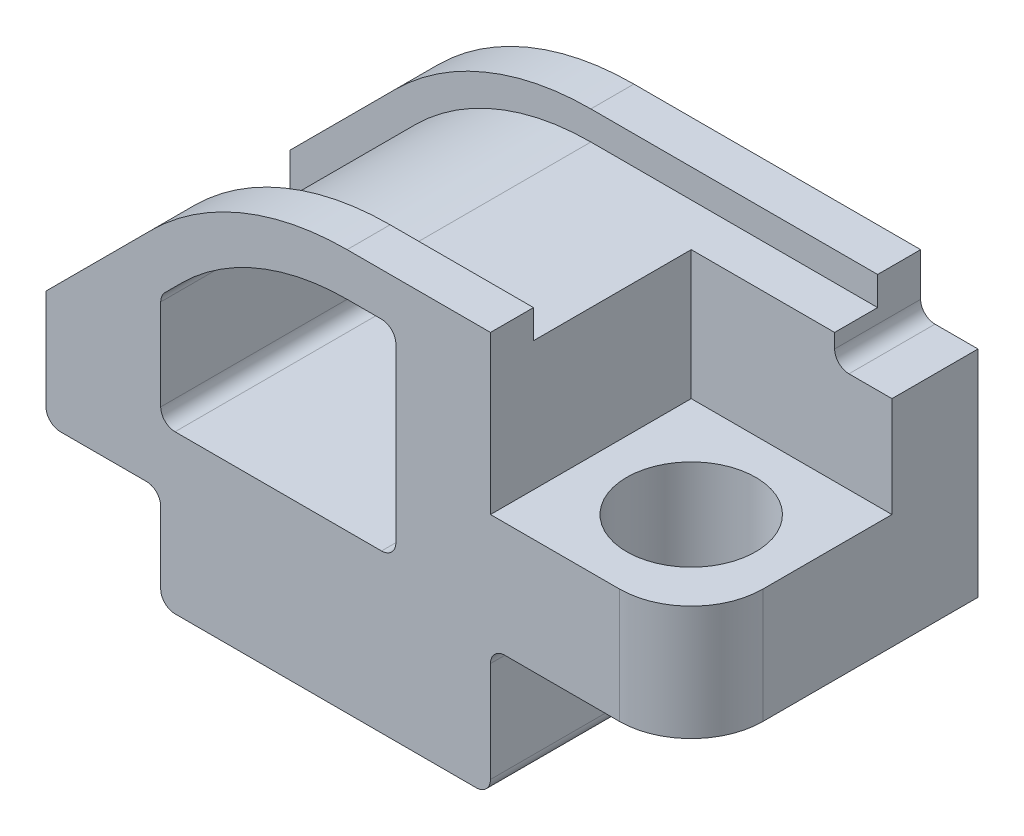
SolidWorks part; units mm, degrees
material "Copper"
ref_plane "Front Plane" through (0, 0, 0) normal (0, 0, 1) x (1, 0, 0)
ref_plane "Top Plane" through (0, 0, 0) normal (0, 1, 0) x (1, 0, 0)
ref_plane "Right Plane" through (0, 0, 0) normal (1, 0, 0) x (0, 0, -1)
sketch "Sketch1" plane through (0, 0, 0) normal (0, 0, 1) x (1, 0, 0)
  line L0 (0, 0) -> (40, 0)
  line L1 (40, 0) -> (40, -35)
  line L2 (40, -35) -> (155, -35)
  line L3 (155, -35) -> (155, 10)
  line L4 (155, 10) -> (225, 10)
  line L5 (225, 10) -> (225, 85)
  line L6 (225, 85) -> (205, 85)
  line L7 (205, 85) -> (205, 105)
  line L8 (205, 105) -> (105, 105)
  line L9 (36.7157, 76.7157) -> (0, 40)
  line L10 (0, 40) -> (0, 0)
  arc A0 (105, 105) -> (36.7157, 76.7157) centre (105, 8.4315) ccw
  point P14 (155, 105)
  point P15 (32.6613, 85)
  dimension "D1" = 35
  dimension "D2" = 115
  dimension "D3" = 45
  dimension "D4" = 70
  dimension "D5" = 75
  dimension "D6" = 140
  dimension "D7" = 20
  dimension "D8" = 100
  dimension "D9" = 225
  dimension "D10" = 40
  dimension "D11" = 45
extrude "Boss-Extrude1" add sketch "Sketch1" along normal mid plane 100
sketch "Sketch2" plane through (0, 0, 50) normal (0, 0, 1) x (1, 0, 0)
  line L15 (40, 58.7868) -> (40, 20)
  line L16 (40, 20) -> (122, 20)
  line L17 (205, 90) -> (105, 90)
  line L18 (47.3223, 66.1091) -> (10.6066, 29.3934)
  line L19 (122, 90) -> (105, 90)
  line L20 (47.3223, 66.1091) -> (40, 58.7868)
  line L21 (122, 20) -> (122, 90)
  line L22 (155, -35) -> (155, 10) construction
  line L23 (40, 0) -> (40, -35) construction
  line L24 (0, 40) -> (0, 0) construction
  arc A4 (105, 90) -> (47.3223, 66.1091) centre (105, 8.4315) ccw
  arc A5 (105, 90) -> (47.3223, 66.1091) centre (105, 8.4315) ccw
  point P10 (0, 20)
  dimension "D2" = 33
  dimension "D1" = 15
extrude "Cut-Extrude1" cut sketch "Sketch2" against normal through all
sketch "Sketch5" plane through (0, 0, 0) normal (0, 0, 1) x (1, 0, 0)
  line L2 (205, 85) -> (205, 105) construction
  line L3 (205, 105) -> (105, 105) construction
  line L4 (205, 95) -> (105, 95)
  line L5 (43.7868, 69.6447) -> (7.0711, 32.9289)
  line L6 (205, 95) -> (105, 95)
  line L7 (43.7868, 69.6447) -> (0, 25.8579)
  line L8 (36.7157, 76.7157) -> (0, 40) construction
  line L9 (0, 40) -> (0, 0) construction
  line L10 (205, 95) -> (205, 105)
  line L11 (205, 105) -> (105, 105)
  line L12 (36.7157, 76.7157) -> (0, 40)
  line L13 (0, 40) -> (0, 25.8579)
  arc A1 (105, 105) -> (36.7157, 76.7157) centre (105, 8.4315) ccw construction
  arc A2 (105, 95) -> (43.7868, 69.6447) centre (105, 8.4315) ccw
  arc A3 (105, 95) -> (43.7868, 69.6447) centre (105, 8.4315) ccw
  arc A4 (105, 105) -> (36.7157, 76.7157) centre (105, 8.4315) ccw
  dimension "D1" = 10
extrude "Cut-Extrude3" cut sketch "Sketch5" against normal mid plane 70
sketch "Sketch6" plane through (0, 105, 0) normal (0, 1, 0) x (1, 0, 0)
  line L1 (225, -50) -> (155, -50)
  line L2 (225, -50) -> (225, 20)
  line L3 (225, 20) -> (155, 20)
  line L4 (155, -50) -> (155, 20)
  dimension "D1" = 70
extrude "Cut-Extrude4" cut sketch "Sketch6" against normal blind 55
sketch "Sketch7" plane through (0, 50, 0) normal (0, 1, 0) x (1, 0, 0)
  line L0 (155, -50) -> (225, 20) construction
  circle A0 centre (190, -15) radius 22.5
  point P6 (0, 0)
  point P7 (190, -15)
  dimension "D1" = 45
extrude "Cut-Extrude5" cut sketch "Sketch7" against normal through all
fillet "Fillet1" radius 25 1 edges at (225, 30, 50)
fillet "Fillet2" radius 5 6 edges at (155, 10, 0) (155, -35, 0) (0, 0, 0) (40, 0, 0) (40, -35, 0) (205, 85, -35)
fillet "Fillet3" radius 5 4 edges at (40, 58.7868, 0) (40, 20, 0) (122, 20, 0) (122, 90, 0)
equation "\"A\"= 225"
equation "\"B\"= 40"
equation "\"C\"= 45"
equation "\"D\"= 45"
equation "\"D9@Sketch1\"=\"A\""
equation "\"D10@Sketch1\"=\"B\""
equation "\"D11@Sketch1\"=\"D\""
equation "\"D1@Sketch7\"=\"C\""
